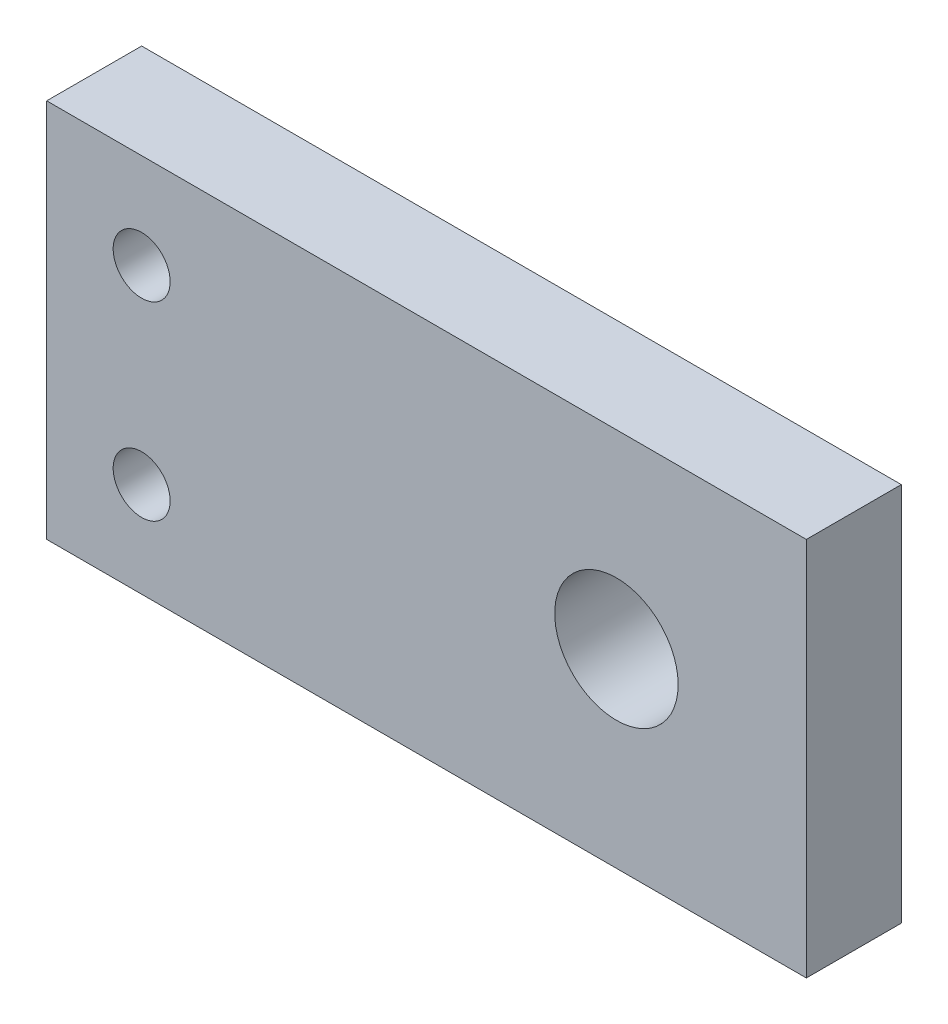
SolidWorks part; units mm, degrees
material "6061 Alloy"
ref_plane "Front Plane" through (0, 0, 0) normal (0, 0, 1) x (1, 0, 0)
ref_plane "Top Plane" through (0, 0, 0) normal (0, 1, 0) x (1, 0, 0)
ref_plane "Right Plane" through (0, 0, 0) normal (1, 0, 0) x (0, 0, -1)
sketch "Sketch1" plane through (0, 0, 0) normal (0, 0, 1) x (1, 0, 0)
  line L1 (0, 0) -> (40, 0)
  line L2 (0, 0) -> (0, 20)
  line L3 (0, 20) -> (40, 20)
  line L4 (40, 0) -> (40, 20)
  dimension "D1" = 20
  dimension "D2" = 40
extrude "Boss-Extrude1" add sketch "Sketch1" along normal blind 5
sketch "Sketch2" plane through (0, 0, 5) normal (0, 0, 1) x (1, 0, 0)
  line L0 (40, 20) -> (0, 20) construction
  line L1 (40, 0) -> (40, 20) construction
  line L2 (0, -2.75) -> (0, 2.75) construction
  circle A0 centre (30, 10) radius 3.25
  circle A1 centre (5, 15) radius 1.5
  circle A2 centre (5, 5) radius 1.5
  dimension "D1" = 6.5
  dimension "D2" = 10
  dimension "D3" = 10
  dimension "D4" = 10
  dimension "D5" = 5
  dimension "D6" = 5
  dimension "D7" = 3
extrude "Cut-Extrude1" cut sketch "Sketch2" against normal blind 5
